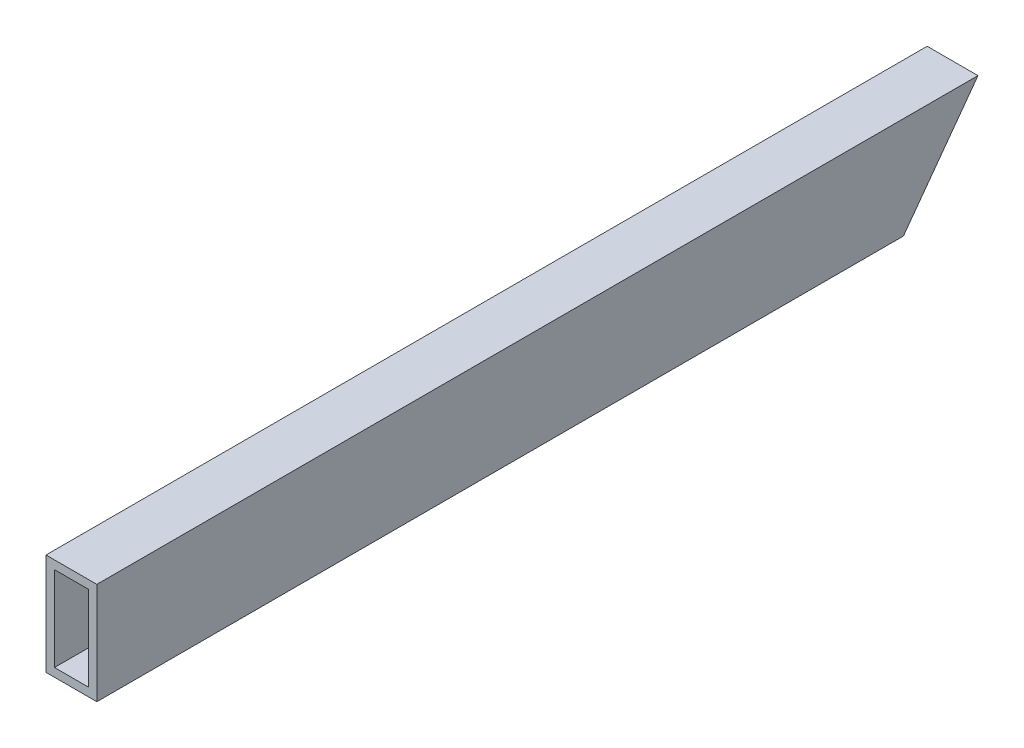
SolidWorks part; units mm, degrees
ref_plane "Front Plane" through (0, 0, 0) normal (0, 0, 1) x (1, 0, 0)
ref_plane "Top Plane" through (0, 0, 0) normal (0, 1, 0) x (1, 0, 0)
ref_plane "Right Plane" through (0, 0, 0) normal (1, 0, 0) x (0, 0, -1)
sketch "Sketch1" plane through (0, 0, 0) normal (0, 0, 1) x (1, 0, 0)
  line L0 (6.35, -15.875) -> (6.35, 15.875)
  line L1 (-9.525, -19.05) -> (9.525, -19.05)
  line L2 (-9.525, -19.05) -> (-9.525, 19.05)
  line L3 (-9.525, 19.05) -> (9.525, 19.05)
  line L4 (9.525, -19.05) -> (9.525, 19.05)
  line L5 (-9.525, -19.05) -> (9.525, 19.05) construction
  line L6 (-9.525, 19.05) -> (9.525, -19.05) construction
  line L7 (-6.35, 15.875) -> (6.35, 15.875)
  line L8 (-6.35, -15.875) -> (-6.35, 15.875)
  line L9 (-6.35, -15.875) -> (6.35, -15.875)
  point P0 (0, 0)
  dimension "D1" = 38.1
  dimension "D2" = 19.05
  dimension "D3" = 3.175
extrude "Boss-Extrude1" add sketch "Sketch1" along normal blind 330.2
sketch "Sketch2" plane through (9.525, 0, 0) normal (1, 0, 0) x (0, 0, -1)
  line L1 (-330.2, -19.05) -> (0, -19.05) construction
  line L4 (0, 19.05) -> (-27.94, -19.05)
  line L5 (-27.94, -19.05) -> (0, -19.05)
  line L6 (0, -19.05) -> (0, 19.05) construction
  line L7 (0, -19.05) -> (0, 19.05)
  dimension "D1" = 27.94
extrude "Cut-Extrude1" cut sketch "Sketch2" against normal through all
